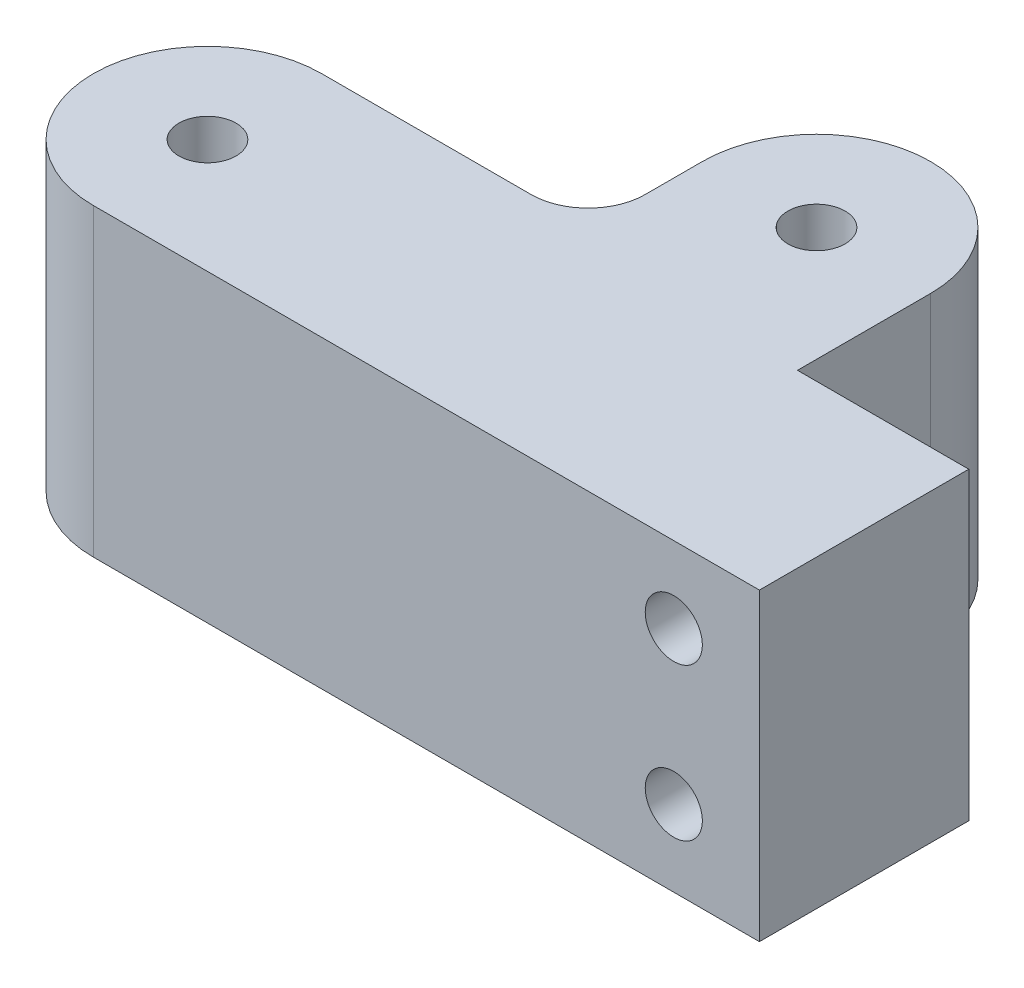
SolidWorks part; units mm, degrees
ref_plane "Front Plane" through (0, 0, 0) normal (0, 0, 1) x (1, 0, 0)
ref_plane "Top Plane" through (0, 0, 0) normal (0, 1, 0) x (1, 0, 0)
ref_plane "Right Plane" through (0, 0, 0) normal (1, 0, 0) x (0, 0, -1)
sketch "Sketch3" plane through (0, 0, 0) normal (0, 1, 0) x (1, 0, 0)
  line L0 (0, 6) -> (20, 6)
  line L1 (14, 12) -> (14, 6)
  line L2 (0, -6) -> (26.8753, -6)
  line L3 (26, 12) -> (26, -6)
  line L5 (26, -6) -> (35, -6)
  line L6 (26, -6) -> (26, 5)
  line L7 (26, 5) -> (35, 5)
  line L8 (35, -6) -> (35, 5)
  circle A0 centre (0, 0) radius 1.5
  circle A1 centre (20, 12) radius 1.5
  circle A2 centre (0, 0) radius 6
  circle A3 centre (20, 12) radius 6
  dimension "D3" = 3
  dimension "D4" = 3
  dimension "D5" = 12
  dimension "D6" = 12
  dimension "D1" = 12
  dimension "D2" = 20
  dimension "D7" = 9
  dimension "D8" = 11
extrude "Boss-Extrude1" add sketch "Sketch3" along normal blind 16 contours A3 L1 L0 | A3 A1 | A3 L0 A2 L2 L3 | A2 A0 | L5 L8 L7 L3 L2
fillet "Fillet1" radius 3 1 edges at (14, 8, -6)
sketch "Sketch4" plane through (0, 0, -5) normal (0, 0, -1) x (-1, 0, 0)
  line L0 (-35, 16) -> (-35, 0) construction
  line L1 (-26, 0) -> (-35, 0) construction
  line L2 (-26, 16) -> (-35, 16) construction
  circle A0 centre (-30.5, 12) radius 1.5
  circle A1 centre (-30.5, 4) radius 1.5
  dimension "D1" = 3
  dimension "D2" = 3
  dimension "D3" = 4.5
  dimension "D4" = 4.5
  dimension "D5" = 4
  dimension "D6" = 4
extrude "Cut-Extrude1" cut sketch "Sketch4" against normal through all
